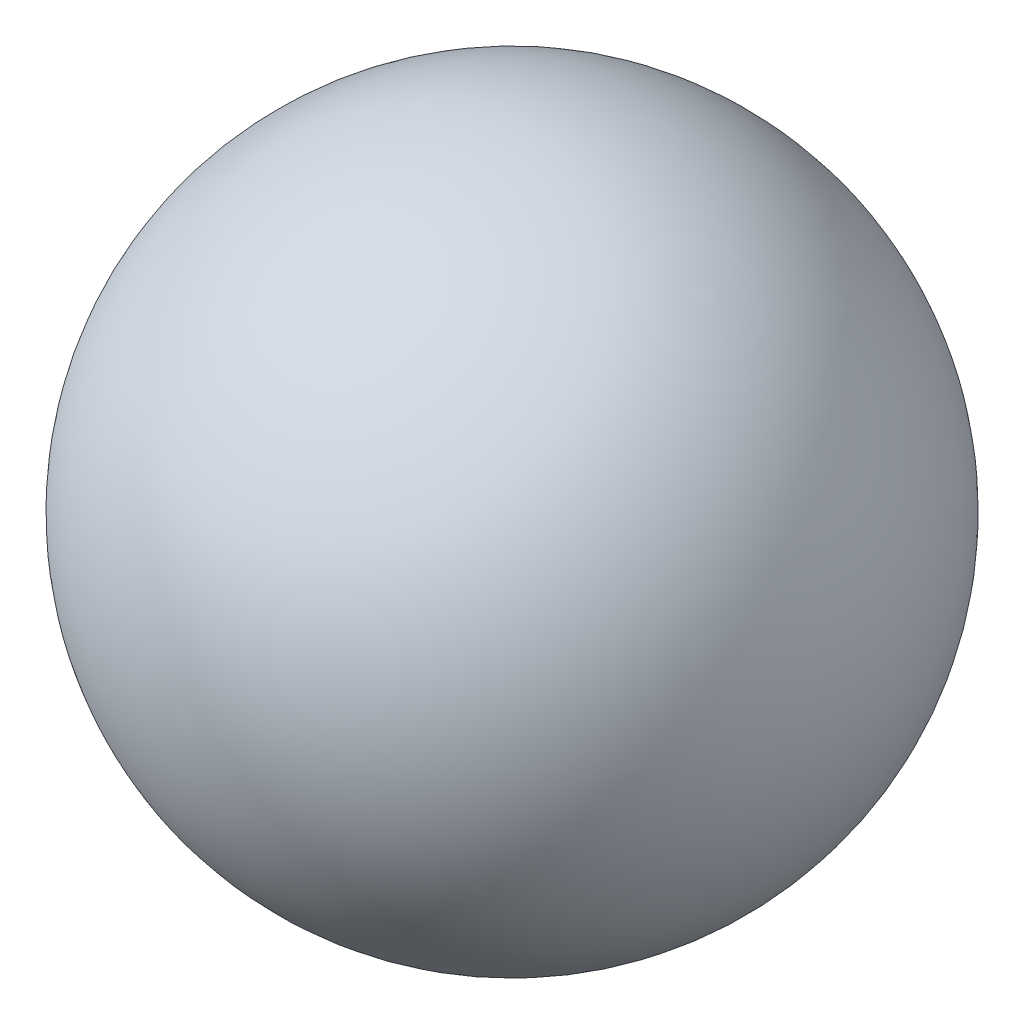
SolidWorks part; units mm, degrees
ref_plane "Front Plane" through (0, 0, 0) normal (0, 0, 1) x (1, 0, 0)
ref_plane "Top Plane" through (0, 0, 0) normal (0, 1, 0) x (1, 0, 0)
ref_plane "Right Plane" through (0, 0, 0) normal (1, 0, 0) x (0, 0, -1)
sketch "Sketch1" plane through (0, 0, 0) normal (0, 1, 0) x (1, 0, 0)
  line L0 (0, -11.43) -> (0, 11.43)
  arc A0 (0, -11.43) -> (0, 11.43) centre (0, 0) ccw
  dimension "D1" = 22.86
revolve "Revolve2" add sketch "Sketch1" angle 360 about L0
